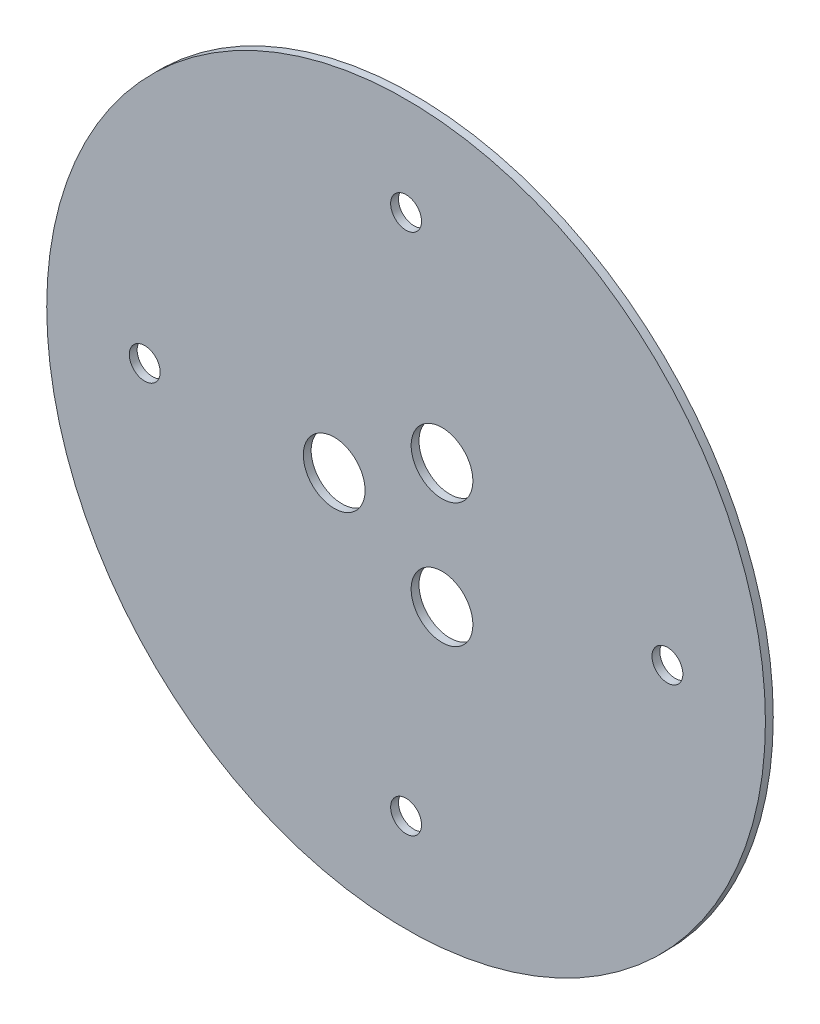
SolidWorks part; units mm, degrees
material "Copper"
ref_plane "Front Plane" through (0, 0, 0) normal (0, 0, 1) x (1, 0, 0)
ref_plane "Top Plane" through (0, 0, 0) normal (0, 1, 0) x (1, 0, 0)
ref_plane "Right Plane" through (0, 0, 0) normal (1, 0, 0) x (0, 0, -1)
sketch "Sketch1" plane through (0, 0, 0) normal (0, 0, 1) x (1, 0, 0)
  circle A0 centre (0, 0) radius 69.85
  dimension "D1" = 139.7
extrude "Boss-Extrude1" add sketch "Sketch1" along normal blind 1.524
sketch "Sketch2" plane through (0, 0, 1.524) normal (0, 0, 1) x (1, 0, 0)
  line L0 (0, -32.245) -> (0, 45.5731) construction
  circle A0 centre (-13.97, 0) radius 6
  circle A2 centre (6.985, 12.0984) radius 6
  circle A3 centre (6.985, -12.0984) radius 6
  point P12 (0, 0)
  dimension "D1" = 12
  dimension "D2" = 13.97
  dimension "D3" = 3
extrude "Cut-Extrude1" cut sketch "Sketch2" against normal blind 2
sketch "Sketch3" plane through (0, 0, 1.524) normal (0, 0, 1) x (1, 0, 0)
  circle A0 centre (50.8, 0) radius 3
  dimension "D1" = 6
  dimension "D2" = 50.8
extrude "Cut-Extrude2" cut sketch "Sketch3" against normal up to next
pattern_circular "CirPattern1" count 4 over 360 about axis through (0, 0, 0) along (0, 0, 1) of "Cut-Extrude2"
